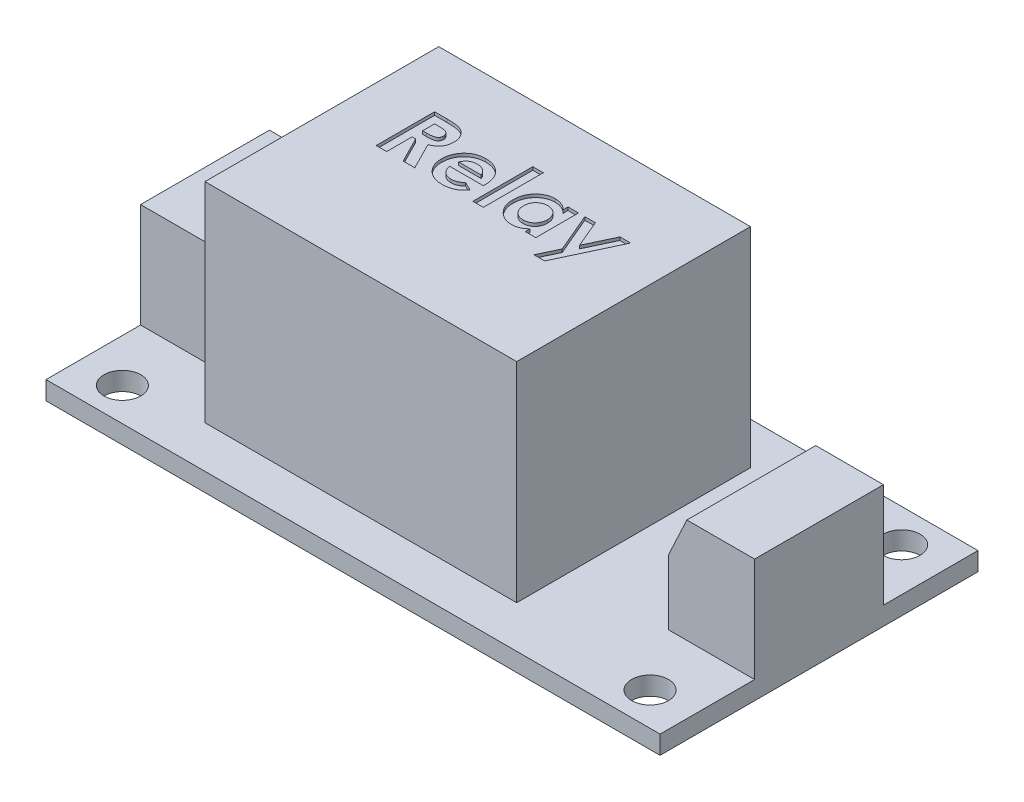
SolidWorks part; units mm, degrees
ref_plane "Front Plane" through (0, 0, 0) normal (0, 0, 1) x (1, 0, 0)
ref_plane "Top Plane" through (0, 0, 0) normal (0, 1, 0) x (1, 0, 0)
ref_plane "Right Plane" through (0, 0, 0) normal (1, 0, 0) x (0, 0, -1)
sketch "Sketch1" plane through (0, 0, 0) normal (0, 1, 0) x (1, 0, 0)
  line L1 (-25.019, -12.954) -> (25.019, -12.954)
  line L2 (-25.019, -12.954) -> (-25.019, 12.954)
  line L3 (-25.019, 12.954) -> (25.019, 12.954)
  line L4 (25.019, -12.954) -> (25.019, 12.954)
  line L5 (-25.019, -12.954) -> (25.019, 12.954) construction
  line L6 (-25.019, 12.954) -> (25.019, -12.954) construction
  point P0 (0, 0)
  dimension "D1" = 25.908
  dimension "D2" = 50.038
extrude "Boss-Extrude1" add sketch "Sketch1" along normal blind 1.5
sketch "Sketch2" plane through (0, 1.5, 0) normal (0, 1, 0) x (1, 0, 0)
  line L0 (0, 0) -> (50000, 0) construction
  line L2 (-15.494, -9.525) -> (9.906, -9.525)
  line L3 (-15.494, -9.525) -> (-15.494, 9.525)
  line L4 (-15.494, 9.525) -> (9.906, 9.525)
  line L5 (9.906, -9.525) -> (9.906, 9.525)
  line L6 (-15.494, -9.525) -> (9.906, 9.525) construction
  line L7 (-15.494, 9.525) -> (9.906, -9.525) construction
  line L8 (-25.019, 12.954) -> (-25.019, -12.954) construction
  point P3 (-2.794, 0)
  dimension "D1" = 19.05
  dimension "D2" = 25.4
  dimension "D3" = 9.525
extrude "Boss-Extrude2" add sketch "Sketch2" along normal blind 17.018
sketch "Sketch3" plane through (0, 1.5, 0) normal (0, 1, 0) x (1, 0, 0)
  line L0 (0, 0) -> (-50000, 0) construction
  line L1 (-25.019, 12.954) -> (-25.019, -12.954) construction
  line L2 (-18.019, -5.25) -> (-25.019, -5.25)
  line L3 (-18.019, -5.25) -> (-18.019, 5.25)
  line L4 (-18.019, 5.25) -> (-25.019, 5.25)
  line L5 (-25.019, -5.25) -> (-25.019, 5.25)
  line L6 (-18.019, -5.25) -> (-25.019, 5.25) construction
  line L7 (-18.019, 5.25) -> (-25.019, -5.25) construction
  line L8 (25.019, -12.954) -> (25.019, 12.954) construction
  line L9 (18.019, -5.25) -> (25.019, -5.25)
  line L10 (18.019, -5.25) -> (18.019, 5.25)
  line L11 (18.019, 5.25) -> (25.019, 5.25)
  line L12 (25.019, -5.25) -> (25.019, 5.25)
  line L13 (18.019, -5.25) -> (25.019, 5.25) construction
  line L14 (18.019, 5.25) -> (25.019, -5.25) construction
  point P3 (-21.519, 0)
  point P10 (21.519, 0)
  dimension "D1" = 10.5
  dimension "D2" = 7
extrude "Boss-Extrude3" add sketch "Sketch3" along normal blind 8.5
chamfer "Chamfer1" distance 3.175 angle 25 2 edges at (18.019, 10, 0) (-18.019, 10, 0)
sketch "Sketch4" plane through (0, 18.518, 0) normal (0, 1, 0) x (1, 0, 0)
  line L0 (-15.494, 0) -> (9.906, 0) construction
  line L1 (-15.494, 9.525) -> (-15.494, -9.525) construction
  line L2 (9.906, -9.525) -> (9.906, 9.525) construction
  text T0 "<b>Relay</b>" font "Century Gothic" height in points 18
extrude "Cut-Extrude1" cut sketch "Sketch4" against normal blind 0.254
sketch "Sketch6" plane through (0, 0, 0) normal (0, -1, 0) x (1, 0, 0)
  line L1 (21.5, 10.25) -> (-21.5, 10.25) construction
  line L2 (21.5, 10.25) -> (21.5, -10.25) construction
  line L3 (21.5, -10.25) -> (-21.5, -10.25) construction
  line L4 (-21.5, 10.25) -> (-21.5, -10.25) construction
  line L5 (21.5, 10.25) -> (-21.5, -10.25) construction
  line L6 (21.5, -10.25) -> (-21.5, 10.25) construction
  circle A0 centre (21.5, -10.25) radius 1.5
  circle A1 centre (-21.5, -10.25) radius 1.5
  circle A2 centre (-21.5, 10.25) radius 1.5
  circle A3 centre (21.5, 10.25) radius 1.5
  point P0 (0, 0)
  dimension "D3" = 3
  dimension "D1" = 20.5
  dimension "D2" = 43
extrude "Cut-Extrude2" cut sketch "Sketch6" against normal through all
